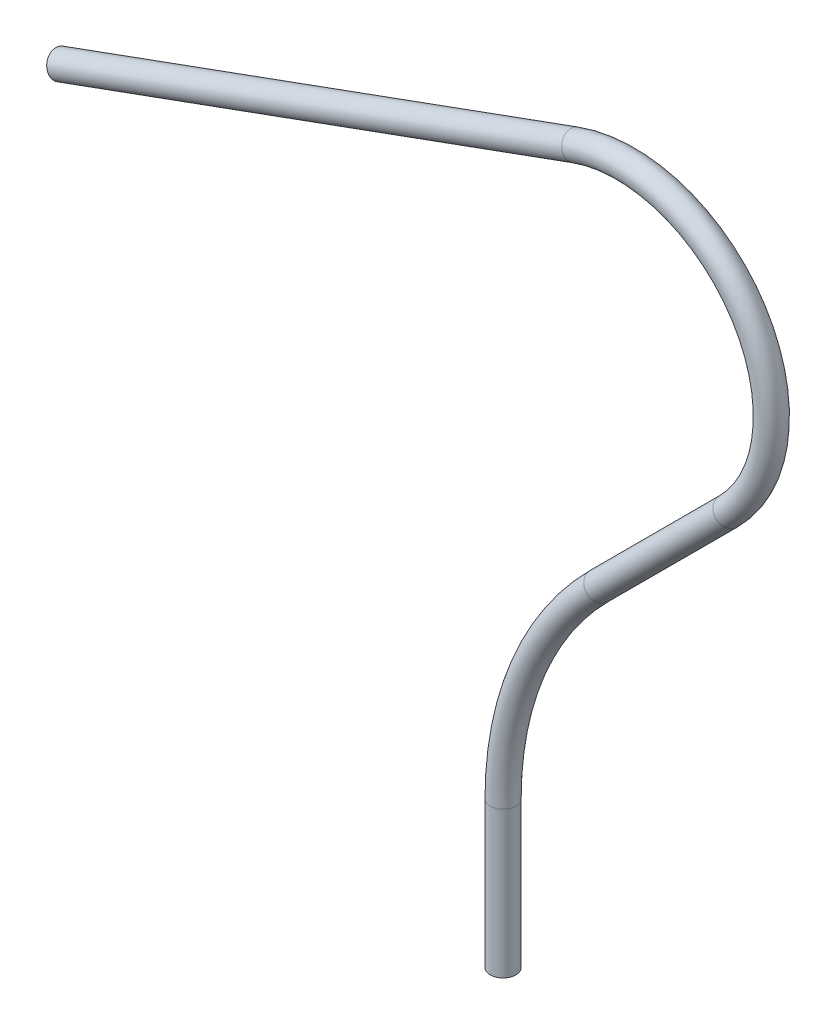
SolidWorks part; units mm, degrees
ref_plane "Alzado" through (0, 0, 0) normal (0, 0, 1) x (1, 0, 0)
ref_plane "Planta" through (0, 0, 0) normal (0, 1, 0) x (1, 0, 0)
ref_plane "Vista lateral" through (0, 0, 0) normal (1, 0, 0) x (0, 0, -1)
sketch "Croquis1" plane through (0, 0, 0) normal (0, 0, 1) x (1, 0, 0)
  line L0 (61.7157, 138.9949) -> (26.3604, 103.6396)
  line L1 (0, 40) -> (0, 0)
  line L2 (19.7507, 204.8669) -> (33.4315, 167.2792) construction
  line L3 (33.4315, 167.2792) -> (61.7157, 138.9949) construction
  line L4 (19.7507, 204.8669) -> (-121.2032, 153.5639)
  arc A0 (19.7507, 204.8669) -> (61.7157, 138.9949) centre (33.4315, 167.2792) cw
  arc A1 (26.3604, 103.6396) -> (0, 40) centre (90, 40) ccw
  dimension "D1" = 40
  dimension "D4" = 90
  dimension "D2" = 150
  dimension "D3" = 50
  dimension "D5" = 40
  dimension "D6" = 155
  dimension "D7" = 135
sketch "Croquis2" plane through (0, 0, 0) normal (0, 1, 0) x (1, 0, 0)
  circle A0 centre (0, 0) radius 3.5
  dimension "D1" = 7
sweep "Barrer1" add profiles "Croquis2" path "Croquis1"
